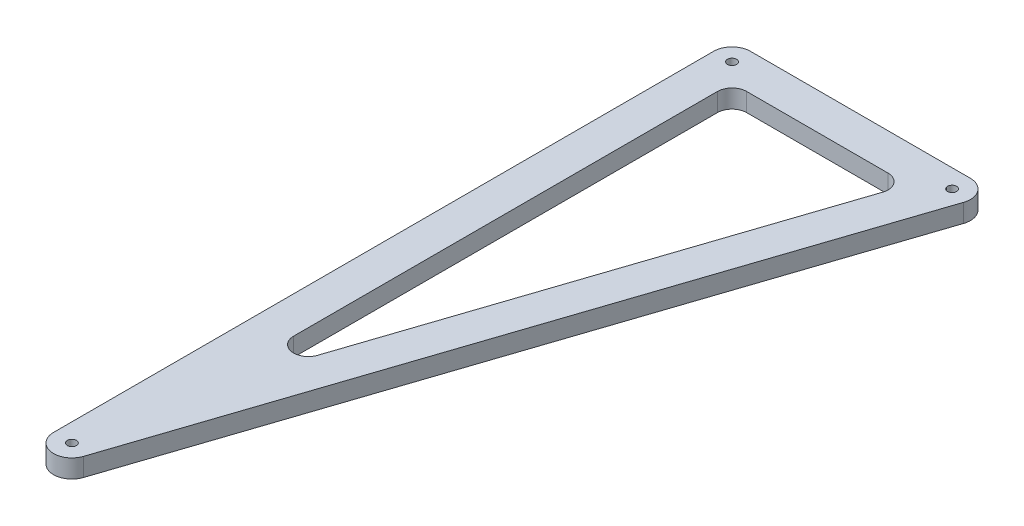
SolidWorks part; units mm, degrees
ref_plane "Front Plane" through (0, 0, 0) normal (0, 0, 1) x (1, 0, 0)
ref_plane "Top Plane" through (0, 0, 0) normal (0, 1, 0) x (1, 0, 0)
ref_plane "Right Plane" through (0, 0, 0) normal (1, 0, 0) x (0, 0, -1)
sketch "Sketch1" plane through (0, 0, 0) normal (0, 1, 0) x (1, 0, 0)
  line L0 (-3.175, 0) -> (-3.175, 114.3)
  line L1 (0, 117.475) -> (38.1, 117.475)
  line L2 (41.1121, 113.296) -> (3.0121, -1.004)
  line L3 (3.175, 108.585) -> (3.175, 35.2174)
  line L4 (8.1247, 34.4142) -> (32.5805, 107.7818)
  line L5 (30.1709, 111.125) -> (5.715, 111.125)
  arc A0 (3.0121, -1.004) -> (-3.175, 0) centre (0, 0) cw
  arc A1 (38.1, 117.475) -> (41.1121, 113.296) centre (38.1, 114.3) cw
  arc A2 (-3.175, 114.3) -> (0, 117.475) centre (0, 114.3) cw
  circle A3 centre (0, 0) radius 0.7874
  circle A4 centre (0, 114.3) radius 0.7874
  circle A5 centre (38.1, 114.3) radius 0.7874
  arc A6 (30.1709, 111.125) -> (32.5805, 107.7818) centre (30.1709, 108.585) cw
  arc A7 (5.715, 111.125) -> (3.175, 108.585) centre (5.715, 108.585) ccw
  arc A8 (3.175, 35.2174) -> (8.1247, 34.4142) centre (5.715, 35.2174) ccw
  point P2 (0, 114.3)
  point P4 (0, 0)
  point P5 (38.1, 114.3)
  point P16 (0, 0)
  point P25 (3.175, 111.125)
  dimension "D4" = 3.175
  dimension "D9" = 1.5748
  dimension "D13" = 2.54
  dimension "D1" = 3.175
  dimension "D2" = 3.175
  dimension "D3" = 3.175
  dimension "D5" = 114.3
  dimension "D6" = 3.175
  dimension "D7" = 38.1
  dimension "D8" = 3.175
  dimension "D10" = 6.35
  dimension "D11" = 6.35
  dimension "D12" = 6.35
extrude "Boss-Extrude1" add sketch "Sketch1" along normal blind 3.175
